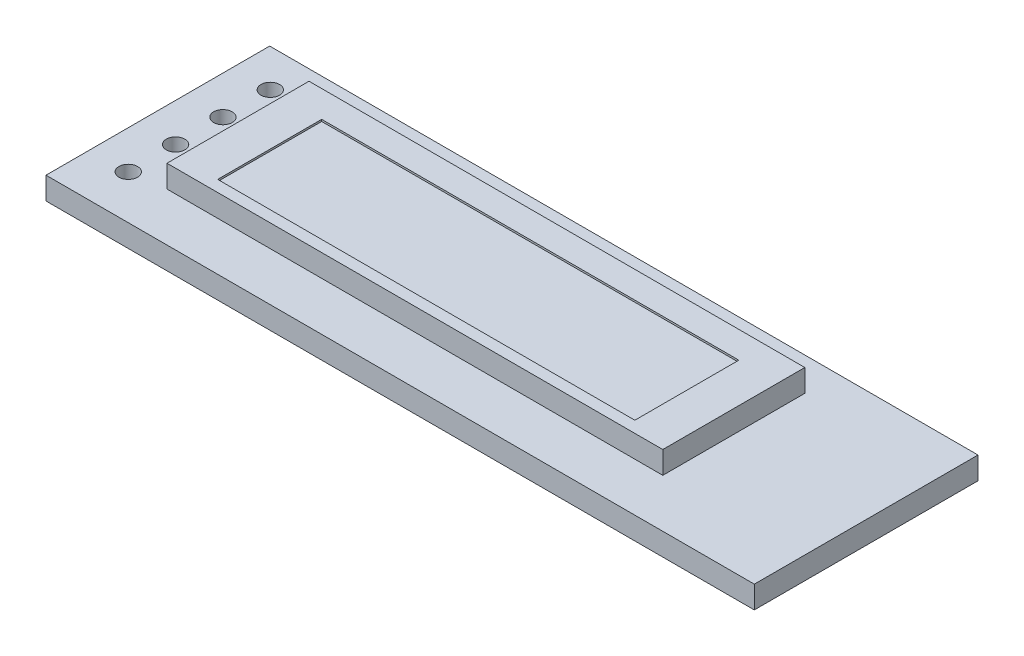
SolidWorks part; units mm, degrees
ref_plane "Front Plane" through (0, 0, 0) normal (0, 0, 1) x (1, 0, 0)
ref_plane "Top Plane" through (0, 0, 0) normal (0, 1, 0) x (1, 0, 0)
ref_plane "Right Plane" through (0, 0, 0) normal (1, 0, 0) x (0, 0, -1)
sketch "Sketch1" plane through (0, 0, 0) normal (0, 1, 0) x (1, 0, 0)
  line L1 (-19, -6) -> (19, -6)
  line L2 (-19, -6) -> (-19, 6)
  line L3 (-19, 6) -> (19, 6)
  line L4 (19, -6) -> (19, 6)
  line L5 (-19, -6) -> (19, 6) construction
  line L6 (-19, 6) -> (19, -6) construction
  point P0 (0, 0)
  dimension "D1" = 38
  dimension "D2" = 12
extrude "Boss-Extrude1" add sketch "Sketch1" along normal blind 1.2
sketch "Sketch2" plane through (0, 1.2, 0) normal (0, 1, 0) x (1, 0, 0)
  line L0 (19, -6) -> (19, 6) construction
  line L1 (11.49, 4.22) -> (-15.11, 4.22)
  line L2 (11.49, 4.22) -> (11.49, -3.4)
  line L3 (11.49, -3.4) -> (-15.11, -3.4)
  line L4 (-15.11, 4.22) -> (-15.11, -3.4)
  line L5 (11.49, 4.22) -> (-15.11, -3.4) construction
  line L6 (11.49, -3.4) -> (-15.11, 4.22) construction
  line L7 (-19, -6) -> (19, -6) construction
  point P0 (-1.81, 0.41)
  dimension "D1" = 7.62
  dimension "D2" = 26.6
  dimension "D3" = 7.51
  dimension "D4" = 2.6
extrude "Boss-Extrude2" add sketch "Sketch2" along normal blind 1.2
sketch "Sketch3" plane through (0, 2.4, 0) normal (0, 1, 0) x (1, 0, 0)
  line L1 (-13, 2.79) -> (9.38, 2.79)
  line L2 (-13, 2.79) -> (-13, -2.79)
  line L3 (-13, -2.79) -> (9.38, -2.79)
  line L4 (9.38, 2.79) -> (9.38, -2.79)
  line L5 (-13, 2.79) -> (9.38, -2.79) construction
  line L6 (-13, -2.79) -> (9.38, 2.79) construction
  point P0 (-1.81, 0)
  dimension "D1" = 22.38
  dimension "D2" = 5.58
extrude "Cut-Extrude1" cut sketch "Sketch3" against normal blind 0.1
sketch "Sketch4" plane through (0, 1.2, 0) normal (0, 1, 0) x (1, 0, 0)
  line L0 (-16.9487, 6) -> (-16.9487, -6) construction
  line L1 (19, 6) -> (-19, 6) construction
  line L2 (-19, -6) -> (19, -6) construction
  line L3 (-19, 0) -> (-16.9487, 0) construction
  line L4 (-19, 6) -> (-19, -6) construction
  circle A0 centre (-16.9487, 3.981) radius 0.5
  circle A1 centre (-16.9487, 1.441) radius 0.5
  circle A2 centre (-16.9487, -1.099) radius 0.5
  circle A3 centre (-16.9487, -3.639) radius 0.5
  dimension "D1" = 1
  dimension "D2" = 2.54
  dimension "D3" = 2.54
  dimension "D4" = 2.54
extrude "Cut-Extrude2" cut sketch "Sketch4" against normal through all
